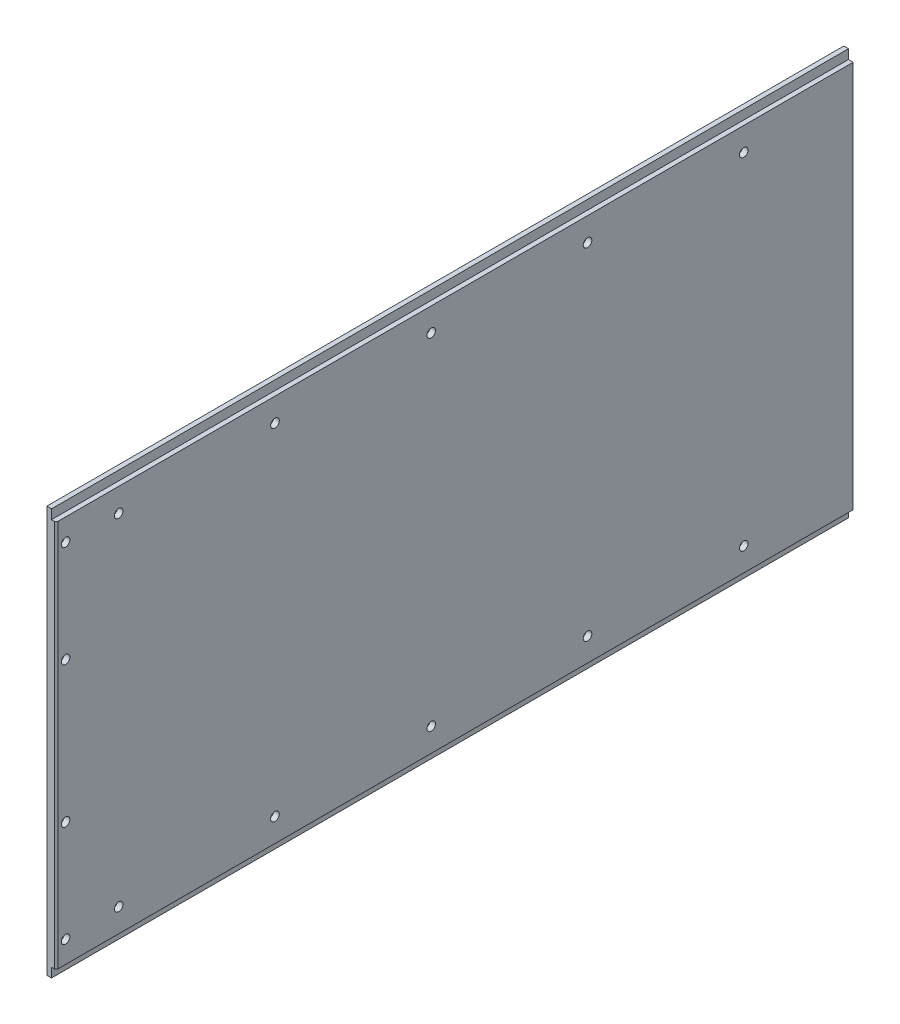
SolidWorks part; units mm, degrees
material "1060 Legierung"
ref_plane "Front Plane" through (0, 0, 0) normal (0, 0, 1) x (1, 0, 0)
ref_plane "Top Plane" through (0, 0, 0) normal (0, 1, 0) x (1, 0, 0)
ref_plane "Right Plane" through (0, 0, 0) normal (1, 0, 0) x (0, 0, -1)
sketch "Sketch1" plane through (0, 0, 0) normal (1, 0, 0) x (0, 0, -1)
  line L0 (0, 0) -> (59.3183, 0) construction
  line L1 (0, 28.1909) -> (0, -28.8956) construction
  line L2 (-255, 130) -> (255, 130)
  line L3 (255, 130) -> (255, -130)
  line L4 (255, -130) -> (-255, -130)
  line L5 (-255, -130) -> (-255, 130)
  dimension "D1" = 510
  dimension "D2" = 260
extrude "Boss-Extrude1" add sketch "Sketch1" along normal blind 6
sketch "Skizze2" plane through (0, 0, 255) normal (0, 0, 1) x (1, 0, 0)
  line L0 (21.4169, 0) -> (-13.9476, 0) construction
  line L1 (3, 130) -> (3, 124)
  line L2 (6, -130) -> (3, -130)
  line L3 (6, -130) -> (6, -124)
  line L4 (6, -124) -> (3, -124)
  line L5 (3, -130) -> (3, -124)
  line L6 (6, 124) -> (3, 124)
  line L7 (6, 130) -> (6, 124)
  line L8 (6, 130) -> (3, 130)
  dimension "D1" = 6
  dimension "D2" = 3
extrude "Schnitt-Linear austragen1" cut sketch "Skizze2" against normal through all
hole_wizard "Formsenkung fur M5 Linsensenkschraube mit Schlitz1" positions "Skizze4" profile "Skizze3" countersink size "M5" standard "Din" end condition through all
sketch "Skizze4" plane through (0, 0, 0) normal (-1, 0, 0) x (0, 0, 1)
  line L0 (0, 0) -> (399.3178, 0) construction
  line L2 (255, 130) -> (255, -130) construction
  point P0 (249, -110)
  point P2 (249, -45)
  dimension "D1" = 45
  dimension "D2" = 110
  dimension "D3" = 6
  dimension "D4" = 6
sketch "Skizze3" plane through (0, -110, 249) normal (0, 1, 0) x (0, 0, 1)
  line L0 (0, 0) -> (0, 6)
  line L1 (0, 6) -> (2.75, 6)
  line L2 (2.75, 6) -> (2.75, 2.45)
  line L3 (2.75, 2.45) -> (5.2, 0)
  line L5 (5.2, 0) -> (0, 0)
  line L6 (-2.75, 2.45) -> (-5.2, 0) construction
  line L11 (0, -6.35) -> (0, 107.95) construction
  dimension "Bohrerdurchmesser" = 5.5
  dimension "Bohrungstiefe" = 6
  dimension "Senkdurchmesser (Oben)" = 10.4
  dimension "Senkwinkel (Oben)" = 90
chamfer "Chamfer1" distance 1 angle 45 1 edges at (6, 0, 255)
hole_wizard "CSK for M5 Countersunk Raised Head Screw1" positions "Sketch3" profile "Sketch2" countersink size "M5" standard "DIN" end condition through all
sketch "Sketch3" plane through (0, 0, 0) normal (-1, 0, 0) x (0, 0, 1)
  line L0 (255, 130) -> (255, -130) construction
  line L1 (255, -130) -> (-255, -130) construction
  point P0 (215, -109)
  dimension "D1" = 40
  dimension "D2" = 21
sketch "Sketch2" plane through (0, -109, 215) normal (0, 1, 0) x (0, 0, 1)
  line L0 (0, 0) -> (0, 6)
  line L1 (0, 6) -> (2.75, 6)
  line L2 (2.75, 6) -> (2.75, 2.45)
  line L3 (2.75, 2.45) -> (5.2, 0)
  line L5 (5.2, 0) -> (0, 0)
  line L6 (-2.75, 2.45) -> (-5.2, 0) construction
  line L11 (0, -6.35) -> (0, 107.95) construction
  dimension "Thru Hole Dia." = 5.5
  dimension "Thru Hole Depth" = 6
  dimension "Near C'Sink Dia." = 10.4
  dimension "Near C'Sink Angle" = 90
pattern_linear "LPattern1" count 5 spacing 100 along (0, 0, -1) of "CSK for M5 Countersunk Raised Head Screw1"
mirror "Spiegeln1" about plane through (0, 0, 0) normal (0, 1, 0) of "LPattern1", "Formsenkung fur M5 Linsensenkschraube mit Schlitz1", "CSK for M5 Countersunk Raised Head Screw1"
